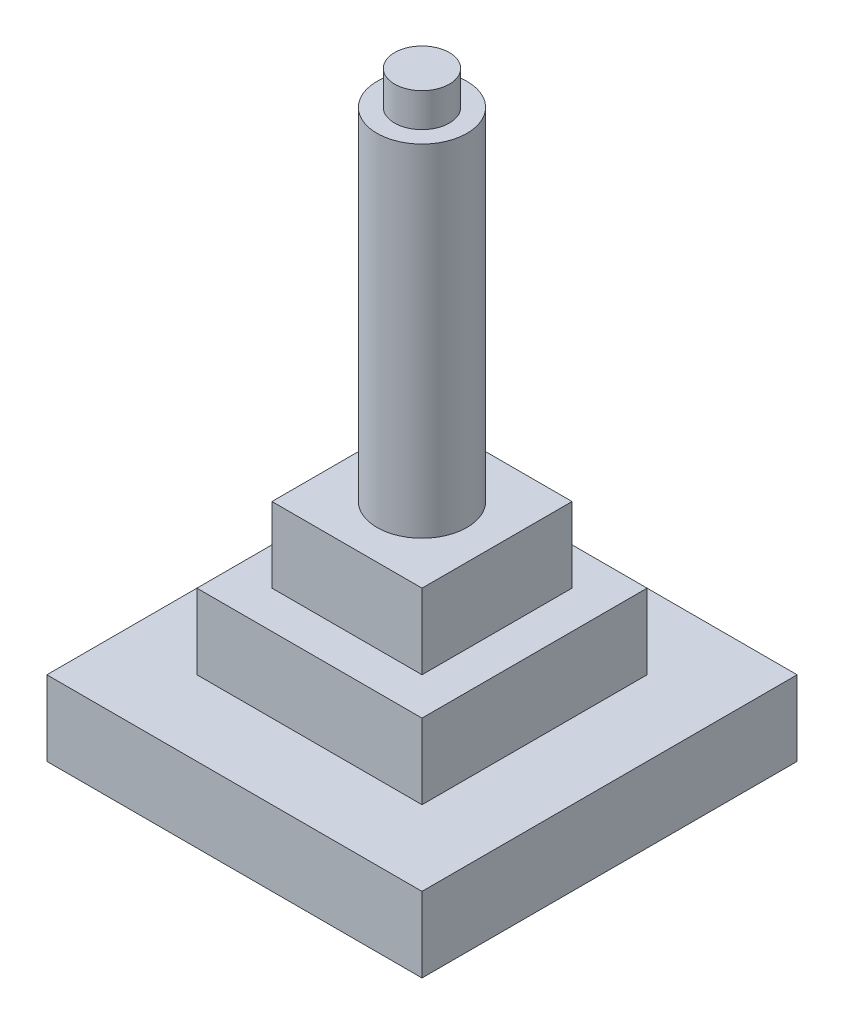
SolidWorks part; units mm, degrees
ref_plane "Front Plane" through (0, 0, 0) normal (0, 0, 1) x (1, 0, 0)
ref_plane "Top Plane" through (0, 0, 0) normal (0, 1, 0) x (1, 0, 0)
ref_plane "Right Plane" through (0, 0, 0) normal (1, 0, 0) x (0, 0, -1)
sketch "Sketch1" plane through (0, 0, 0) normal (0, 1, 0) x (1, 0, 0)
  line L1 (-250, -250) -> (250, -250)
  line L2 (-250, -250) -> (-250, 250)
  line L3 (-250, 250) -> (250, 250)
  line L4 (250, -250) -> (250, 250)
  line L5 (-250, -250) -> (250, 250) construction
  line L6 (-250, 250) -> (250, -250) construction
  point P0 (0, 0)
  dimension "D1" = 500
extrude "Boss-Extrude1" add sketch "Sketch1" along normal blind 100
sketch "Sketch2" plane through (0, 100, 0) normal (0, 1, 0) x (1, 0, 0)
  line L1 (-150, -150) -> (150, -150)
  line L2 (-150, -150) -> (-150, 150)
  line L3 (-150, 150) -> (150, 150)
  line L4 (150, -150) -> (150, 150)
  line L5 (-150, -150) -> (150, 150) construction
  line L6 (-150, 150) -> (150, -150) construction
  point P0 (0, 0)
  dimension "D1" = 300
extrude "Boss-Extrude2" add sketch "Sketch2" along normal blind 100
sketch "Sketch3" plane through (0, 200, 0) normal (0, 1, 0) x (1, 0, 0)
  line L1 (-100, -100) -> (100, -100)
  line L2 (-100, -100) -> (-100, 100)
  line L3 (-100, 100) -> (100, 100)
  line L4 (100, -100) -> (100, 100)
  line L5 (-100, -100) -> (100, 100) construction
  line L6 (-100, 100) -> (100, -100) construction
  point P0 (0, 0)
  dimension "D1" = 200
extrude "Boss-Extrude3" add sketch "Sketch3" along normal blind 100
sketch "Sketch4" plane through (0, 300, 0) normal (0, 1, 0) x (1, 0, 0)
  circle A0 centre (0, 0) radius 60
  dimension "D1" = 120
extrude "Boss-Extrude4" add sketch "Sketch4" along normal blind 455
sketch "Sketch5" plane through (0, 755, 0) normal (0, 1, 0) x (1, 0, 0)
  circle A0 centre (0, 0) radius 36.5
  dimension "D1" = 73
extrude "Boss-Extrude5" add sketch "Sketch5" along normal blind 45
